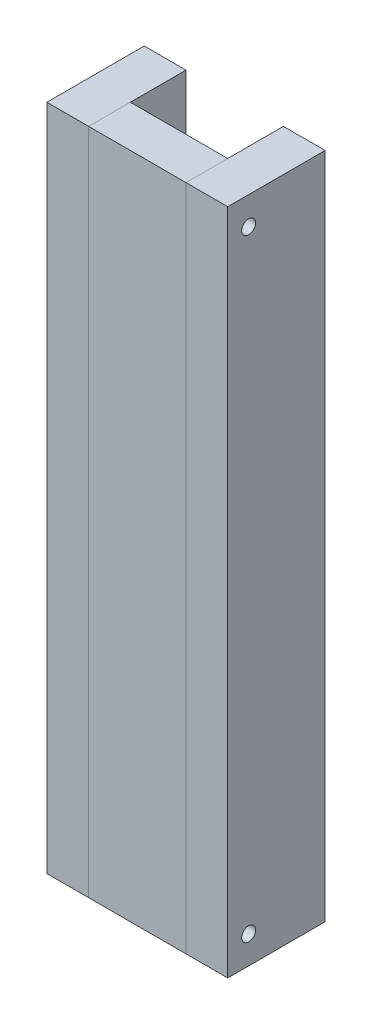
SolidWorks part; units mm, degrees
material "Custom Plastic"
ref_plane "X-Y Datum" through (0, 0, 0) normal (0, 0, 1) x (1, 0, 0)
ref_plane "X-Z Datum" through (0, 0, 0) normal (0, 1, 0) x (1, 0, 0)
ref_plane "Y-Z Datum" through (0, 0, 0) normal (1, 0, 0) x (0, 0, -1)
sketch "Sketch1" plane through (0, 0, 0) normal (0, 0, 1) x (1, 0, 0)
  line L1 (44.45, 304.8) -> (-44.45, 304.8)
  line L2 (44.45, 304.8) -> (44.45, -304.8)
  line L3 (44.45, -304.8) -> (-44.45, -304.8)
  line L4 (-44.45, 304.8) -> (-44.45, -304.8)
  line L5 (44.45, 304.8) -> (-44.45, -304.8) construction
  line L6 (44.45, -304.8) -> (-44.45, 304.8) construction
  point P0 (0, 0)
  dimension "D1" = 609.6
  dimension "D2" = 88.9
extrude "Boss-Extrude1" add sketch "Sketch1" against normal blind 38.1
sketch "Sketch2" plane through (0, 304.8, 0) normal (0, 1, 0) x (1, 0, 0)
  line L1 (44.45, 0) -> (82.55, 0)
  line L2 (44.45, 0) -> (44.45, 88.9)
  line L3 (44.45, 88.9) -> (82.55, 88.9)
  line L4 (82.55, 0) -> (82.55, 88.9)
  line L5 (-44.45, 0) -> (-82.55, 0)
  line L6 (-44.45, 0) -> (-44.45, 88.9)
  line L7 (-44.45, 88.9) -> (-82.55, 88.9)
  line L8 (-82.55, 0) -> (-82.55, 88.9)
  dimension "D1" = 88.9
  dimension "D2" = 38.1
extrude "Boss-Extrude2" add sketch "Sketch2" against normal blind 609.6 separate body
sketch "Sketch3" plane through (-82.55, 0, 0) normal (-1, 0, 0) x (0, 0, 1)
  line L0 (-38.1, 304.8) -> (0, 304.8) construction
  line L1 (-88.9, 304.8) -> (0, 304.8) construction
  line L2 (-88.9, -304.8) -> (0, -304.8) construction
  circle A0 centre (-19.05, 279.4) radius 6.35
  circle A1 centre (-19.05, -279.4) radius 6.35
  point P7 (-19.05, 304.8)
  dimension "D1" = 12.7
  dimension "D2" = 25.4
  dimension "D3" = 25.4
extrude "Cut-Extrude1" cut sketch "Sketch3" against normal blind 76.2
ref_plane "Plane1" through (0, 0, 0) normal (-1, 0, 0) x (0, 0, 1)
mirror "Mirror1" about plane through (0, 0, 0) normal (-1, 0, 0) of "Cut-Extrude1"
